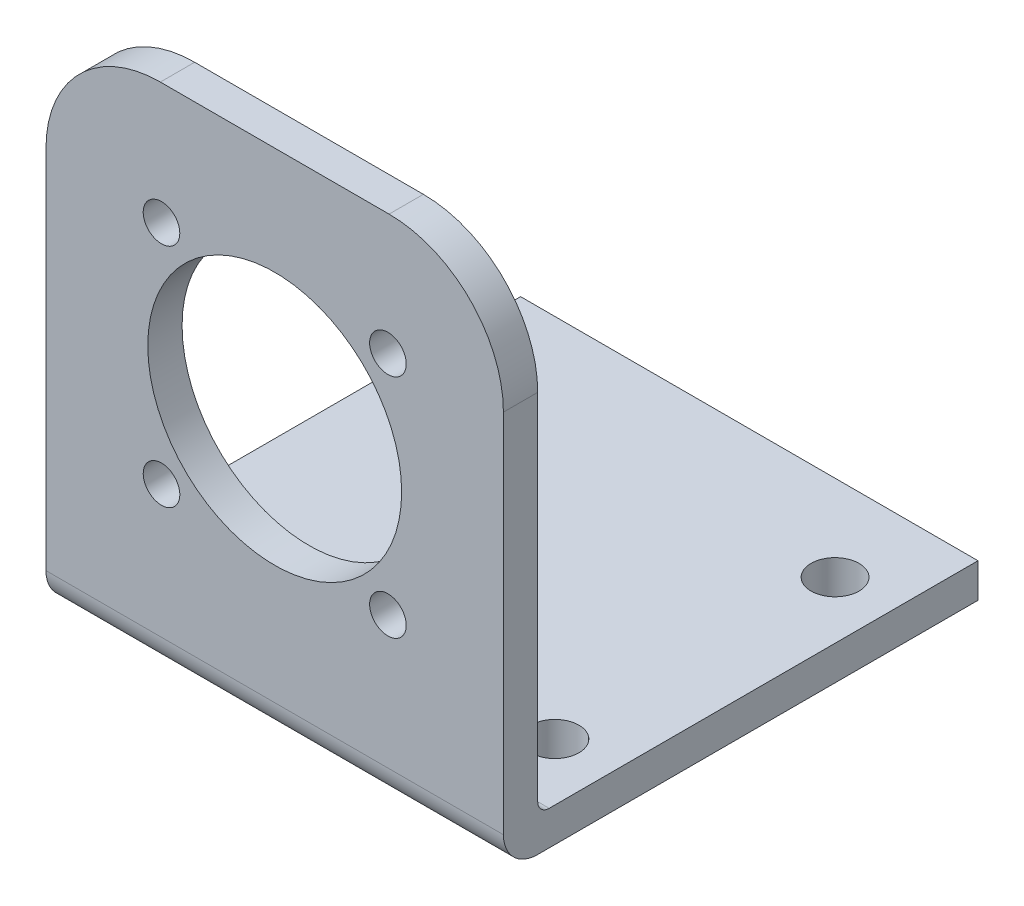
SolidWorks part; units mm, degrees
ref_plane "前视基准面" through (0, 0, 0) normal (0, 0, 1) x (1, 0, 0)
ref_plane "上视基准面" through (0, 0, 0) normal (0, 1, 0) x (1, 0, 0)
ref_plane "右视基准面" through (0, 0, 0) normal (1, 0, 0) x (0, 0, -1)
other "Configuration Table"
sketch "草图1" plane through (0, 0, 0) normal (0, 0, 1) x (1, 0, 0)
  line L0 (0, 0) -> (0, 20.5) construction
  line L1 (-20, 20.5) -> (20, 20.5)
  line L2 (-20, 20.5) -> (-20, -24.5)
  line L3 (-20, -24.5) -> (20, -24.5)
  line L4 (20, 20.5) -> (20, -24.5)
  line L5 (-20, 20) -> (0, 0) construction
  line L6 (0, 0) -> (20, -20) construction
  line L7 (0, 0) -> (-20, -20) construction
  line L8 (20, 20) -> (0, 0) construction
  line L9 (0, 0) -> (20, 0) construction
  circle A0 centre (0, 0) radius 11.1
  circle A1 centre (0, 0) radius 14 construction
  circle A2 centre (-9.8995, 9.8995) radius 1.6
  circle A6 centre (9.8995, 9.8995) radius 1.6
  circle A7 centre (-9.8995, -9.8995) radius 1.6
  circle A8 centre (9.8995, -9.8995) radius 1.6
  point P7 (0, 20.5)
  point P22 (-9.8995, 9.8995)
  dimension "D1" = 22.2
  dimension "D5" = 28
  dimension "D6" = 45
  dimension "D7" = 3.2
  dimension "D2" = 20.5
  dimension "D3" = 40
  dimension "D4" = 45
extrude "凸台-拉伸1" add sketch "草图1" along normal blind 3
sketch "草图2" plane through (0, 0, 3) normal (0, 0, 1) x (1, 0, 0)
  line L0 (-20, 20.5) -> (-20, -24.5) construction
  line L2 (-20, -21.5) -> (20, -21.5)
  line L3 (-20, -21.5) -> (-20, -24.5)
  line L4 (-20, -24.5) -> (20, -24.5)
  line L5 (20, -21.5) -> (20, -24.5)
  dimension "D1" = 3
extrude "凸台-拉伸2" add sketch "草图2" against normal blind 41.5
sketch "草图3" plane through (0, -21.5, 0) normal (0, 1, 0) x (1, 0, 0)
  line L0 (0, 38.5) -> (0, 0) construction
  line L1 (20, 38.5) -> (-20, 38.5) construction
  circle A2 centre (-15, 31) radius 2.1
  circle A3 centre (15, 31) radius 2.1
  circle A4 centre (15, 6.5) radius 2.1
  circle A5 centre (-15, 6.5) radius 2.1
  dimension "D1" = 15
  dimension "D2" = 4.2
  dimension "D3" = 7.5
  dimension "D4" = 24.5
  dimension "D5" = 15
  dimension "D6" = 24.5
  dimension "D7" = 30
extrude "切除-拉伸1" cut sketch "草图3" against normal through all
fillet "圆角1" radius 10 2 edges at (-20, 20.5, 1.5) (20, 20.5, 1.5)
fillet "圆角3" radius 3 1 edges at (0, -24.5, 3)
fillet "圆角4" radius 1 1 edges at (0, -21.5, 0)
equation "\"3mian\"=10"
